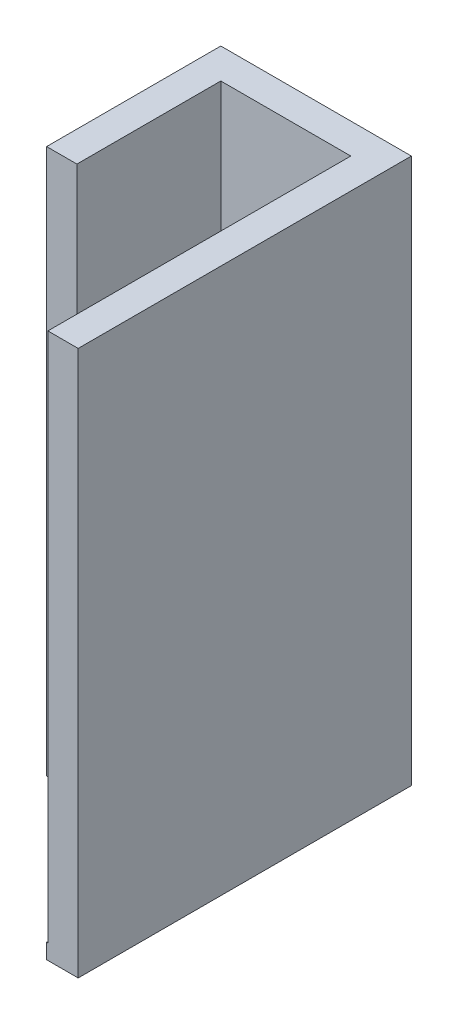
SolidWorks part; units mm, degrees
ref_plane "Front Plane" through (0, 0, 0) normal (0, 0, 1) x (1, 0, 0)
ref_plane "Top Plane" through (0, 0, 0) normal (0, 1, 0) x (1, 0, 0)
ref_plane "Right Plane" through (0, 0, 0) normal (1, 0, 0) x (0, 0, -1)
sketch "Sketch1" plane through (0, 0, 0) normal (0, 1, 0) x (1, 0, 0)
  line L0 (-304.8, 0) -> (-304.8, 1752.6)
  line L1 (-304.8, 1752.6) -> (1612.9, 1752.6)
  line L2 (0, 0) -> (0, 1447.8)
  line L3 (0, 1447.8) -> (1308.1, 1447.8)
  line L4 (1308.1, 1447.8) -> (1308.1, -1600.2)
  line L5 (1612.9, 1752.6) -> (1612.9, -1600.2)
  line L6 (0, 0) -> (-304.8, 0)
  line L7 (1308.1, -1600.2) -> (1612.9, -1600.2)
  dimension "D1" = 1308.1
  dimension "D2" = 1447.8
  dimension "D3" = 3048
  dimension "D4" = 304.8
extrude "Boss-Extrude1" add sketch "Sketch1" along normal blind 5486.4
sketch "Sketch2" plane through (0, 0, 0) normal (0, 1, 0) x (1, 0, 0)
  line L0 (0, 0) -> (12.7, 0)
  line L1 (12.7, 0) -> (12.7, 1435.1)
  line L2 (12.7, 1435.1) -> (1295.4, 1435.1)
  line L3 (1295.4, 1435.1) -> (1295.4, -1600.2)
  line L4 (1308.1, -1600.2) -> (1295.4, -1600.2)
  line L5 (0, 0) -> (0, 1447.8) construction
  line L6 (0, 1447.8) -> (1308.1, 1447.8) construction
  line L7 (1308.1, 1447.8) -> (1308.1, -1600.2) construction
  dimension "D1" = 12.7
  dimension "D2" = 12.7
  dimension "D3" = 12.7
extrude "Extrude-Thin1" add sketch "Sketch2" along normal blind 152.4 thin thin type one direction wall 2.54
